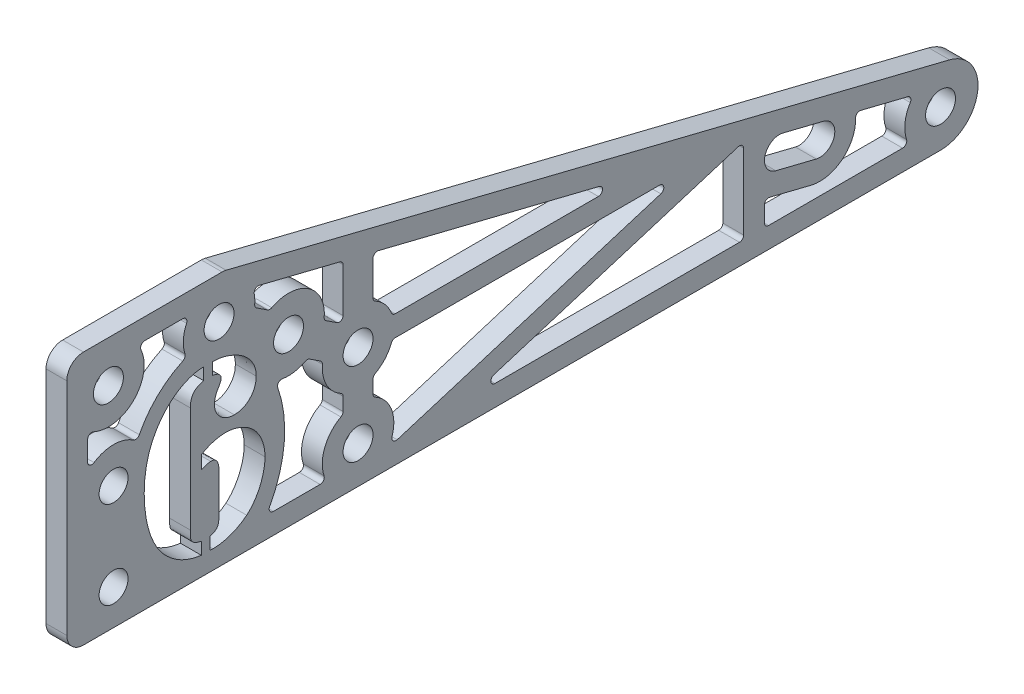
SolidWorks part; units mm, degrees
material "Acrylic (Medium-high impact)"
ref_plane "Front Plane" through (0, 0, 0) normal (0, 0, 1) x (1, 0, 0)
ref_plane "Top Plane" through (0, 0, 0) normal (0, 1, 0) x (1, 0, 0)
ref_plane "Right Plane" through (0, 0, 0) normal (1, 0, 0) x (0, 0, -1)
sketch "Sketch1" plane through (0, 0, 0) normal (1, 0, 0) x (0, 0, -1)
  line L0 (0, 6.35) -> (0, -6.35) construction
  line L1 (0, -6.35) -> (88.9, -6.35) construction
  line L2 (88.9, -6.35) -> (0, 6.35) construction
  line L3 (0, 6.35) -> (88.9, 6.35) construction
  line L4 (88.9, 6.35) -> (88.9, -6.35) construction
  line L5 (-20.1358, 26.5952) -> (90.2764, -0.8032)
  line L6 (0, -12.065) -> (88.9, -12.065)
  line L7 (-20.7475, 26.67) -> (-41.91, 26.67)
  line L8 (-44.45, 24.13) -> (-44.45, -9.525)
  line L9 (-41.91, -12.065) -> (0, -12.065)
  line L11 (0, 6.35) -> (-10.6066, 13.335) construction
  line L12 (-10.6066, 13.335) -> (-21.2132, 20.32) construction
  line L13 (-21.2132, 20.32) -> (-38.1, 20.32) construction
  circle A0 centre (0, 6.35) radius 2.286
  circle A1 centre (0, -6.35) radius 2.286
  circle A2 centre (88.9, -6.35) radius 2.286
  circle A3 centre (0, -6.35) radius 5.715 construction
  circle A4 centre (0, 6.35) radius 5.715 construction
  circle A5 centre (88.9, -6.35) radius 5.715 construction
  circle A6 centre (88.9, 6.35) radius 2.286 construction
  circle A7 centre (88.9, 6.35) radius 5.715 construction
  arc A8 (88.9, -12.065) -> (90.2764, -0.8032) centre (88.9, -6.35) ccw
  arc A9 (-20.7475, 26.67) -> (-20.1358, 26.5952) centre (-20.7475, 24.13) cw
  arc A10 (-44.45, -9.525) -> (-41.91, -12.065) centre (-41.91, -9.525) ccw
  arc A12 (-41.91, 26.67) -> (-44.45, 24.13) centre (-41.91, 24.13) ccw
  circle A13 centre (-21.2132, 20.32) radius 2.286
  circle A14 centre (-10.6066, 13.335) radius 2.286
  circle A15 centre (-38.1, 20.32) radius 2.286
  dimension "D1" = 4.572
  dimension "D4" = 11.43
  dimension "D5" = 2.54
  dimension "D7" = 6.35
  dimension "D9" = 32.385
  dimension "D11" = 6.35
  dimension "D2" = 12.7
  dimension "D3" = 88.9
  dimension "D6" = 44.45
  dimension "D8" = 6.35
  dimension "D10" = 12.7
extrude "Boss-Extrude1" add sketch "Sketch1" along normal blind 3.175
sketch "Sketch2" plane through (3.175, 0, 0) normal (1, 0, 0) x (0, 0, -1)
  line L0 (-35.1004, 12.065) -> (-44.45, 12.065) construction
  line L1 (-44.45, 24.13) -> (-44.45, -9.525) construction
  line L2 (-37.3103, 6.6801) -> (-37.3103, -6.6801) construction
  line L3 (-37.3103, 8.89) -> (-37.3103, 12.065) construction
  line L5 (-37.3103, -8.89) -> (-37.3103, -12.065) construction
  line L6 (-41.91, -12.065) -> (88.9, -12.065) construction
  line L7 (-35.1004, 12.065) -> (-35.1004, -12.065) construction
  line L8 (-39.5202, 12.065) -> (-39.5202, -12.065) construction
  line L9 (64.3105, 0.0135) -> (70.4736, -1.5158) construction
  line L10 (64.8611, 2.2322) -> (71.0241, 0.7029)
  line L11 (63.7599, -2.2052) -> (69.923, -3.7345)
  line L12 (90.2764, -0.8032) -> (-20.1358, 26.5952) construction
  circle A0 centre (-37.3103, 6.6801) radius 2.2099
  circle A1 centre (-37.3103, -6.6801) radius 2.2099
  circle A2 centre (0, -6.35) radius 2.286 construction
  arc A3 (64.8611, 2.2322) -> (63.7599, -2.2052) centre (64.3105, 0.0135) ccw
  arc A4 (69.923, -3.7345) -> (71.0241, 0.7029) centre (70.4736, -1.5158) ccw
  circle A5 centre (0, 6.35) radius 2.286 construction
  circle A6 centre (88.9, -6.35) radius 2.286 construction
  point P11 (67.392, -0.7512)
  dimension "D3" = 4.4198
  dimension "D1" = 3.175
  dimension "D2" = 35.1004
  dimension "D4" = 24.13
  dimension "D5" = 3.175
  dimension "D6" = 6.35
  dimension "D7" = 19.05
extrude "Cut-Extrude1" cut sketch "Sketch2" against normal through all
sketch "Sketch3" plane through (3.175, 0, 0) normal (1, 0, 0) x (0, 0, -1)
  line L0 (-41.275, 23.495) -> (-20.8251, 23.495) construction
  line L2 (-20.8251, 23.495) -> (88.9, -3.733) construction
  line L3 (88.9, -3.733) -> (88.9, -8.89) construction
  line L4 (88.9, -8.89) -> (-41.275, -8.89) construction
  line L5 (-41.275, -8.89) -> (-41.275, 23.495) construction
  line L6 (-44.45, 24.13) -> (-44.45, -9.525) construction
  line L9 (90.2764, -0.8032) -> (-20.1358, 26.5952) construction
  line L10 (-41.91, -12.065) -> (88.9, -12.065) construction
  line L11 (-20.7475, 26.67) -> (-41.91, 26.67) construction
  circle A0 centre (-37.3103, 6.6801) radius 5.461 construction
  circle A1 centre (-37.3103, -6.6801) radius 5.461 construction
  circle A2 centre (-10.6066, 13.335) radius 5.461 construction
  circle A3 centre (0, 6.35) radius 5.461 construction
  circle A4 centre (0, -6.35) radius 5.461 construction
  circle A5 centre (88.9, -6.35) radius 5.461 construction
  circle A6 centre (0, -6.35) radius 2.286 construction
  circle A7 centre (-21.2132, 20.32) radius 5.461 construction
  circle A8 centre (-21.2132, 20.32) radius 2.286 construction
  text T0 "6" font "Stencil" height 24.13
  point P8 (-31.3288, 26.67)
  point P14 (88.9, -6.35)
  dimension "D7" = 3.175
  dimension "D1" = 3.175
  dimension "D2" = 3.175
  dimension "D4" = 3.175
  dimension "D5" = 3.175
extrude "Cut-Extrude2" cut sketch "Sketch3" against normal through all
sketch "Sketch4" plane through (3.175, 0, 0) normal (1, 0, 0) x (0, 0, -1)
  line L0 (-41.275, 23.495) -> (-20.8251, 23.495) construction
  line L1 (-7.3953, 8.483) -> (-5.7259, 7.3836)
  line L2 (2.286, -0.9994) -> (2.286, 0.9994)
  line L3 (2.286, 11.7006) -> (2.286, 16.9482)
  line L4 (-2.286, 11.6673) -> (-2.286, 18.3979)
  line L5 (88.9, -3.733) -> (88.9, -8.89) construction
  line L6 (-41.275, -8.89) -> (-41.275, 23.495) construction
  line L7 (-4.8807, 12.3014) -> (-3.1835, 11.1837)
  line L8 (-13.8179, 18.187) -> (-15.4872, 19.2864)
  line L9 (-15.07, 22.0669) -> (-2.7681, 19.0142)
  line L10 (88.9, -8.89) -> (-41.275, -8.89) construction
  line L11 (88.9, -3.733) -> (88.9, -8.89) construction
  line L12 (-41.275, 14.7784) -> (-41.275, 11.7864)
  line L13 (-32.5584, 23.495) -> (-26.7548, 23.495)
  line L14 (5.6764, 7.9375) -> (36.674, 7.9375)
  line L15 (-12.9295, -8.89) -> (-5.7907, -8.89)
  line L16 (-2.286, 0.9994) -> (-2.286, -0.9994)
  line L17 (62.9952, -5.2867) -> (69.1583, -6.8161) construction
  line L18 (62.0245, -5.8577) -> (62.0245, -8.255)
  line L19 (76.7196, -0.7104) -> (83.8915, -2.4901)
  line L20 (62.6595, -8.89) -> (83.1093, -8.89)
  line L21 (62.8124, -5.2414) -> (69.1583, -6.8161)
  line L22 (20.9031, -8.89) -> (58.2145, -8.89)
  line L23 (-20.8251, 23.495) -> (88.9, -3.733) construction
  line L24 (5.6764, 4.7625) -> (46.0273, 4.7625)
  line L25 (3.0739, 17.5645) -> (36.8269, 9.1888)
  line L33 (0, 6.35) -> (5.6764, 6.35) construction
  line L34 (5.6764, 6.35) -> (5.6764, 7.9375) construction
  line L35 (5.6764, 6.35) -> (5.6764, 4.7625) construction
  line L36 (58.8495, 3.2273) -> (58.8495, -8.255)
  line L40 (5.9775, -8.8619) -> (46.2141, 3.5206)
  line L41 (58.0277, 3.8342) -> (20.7163, -7.6481)
  circle A0 centre (-37.3103, 6.6801) radius 5.461 construction
  circle A1 centre (-21.2132, 20.32) radius 5.461 construction
  arc A2 (62.0245, -5.8577) -> (62.8124, -5.2414) centre (62.6595, -5.8577) cw
  circle A4 centre (-38.1, 20.32) radius 5.461 construction
  circle A5 centre (-10.6066, 13.335) radius 5.461 construction
  circle A6 centre (88.9, -6.35) radius 5.461 construction
  arc A7 (-11.5416, 7.9546) -> (-8.0426, 8.5133) centre (-10.6066, 13.335) ccw
  circle A8 centre (-10.6066, 13.335) radius 2.286 construction
  circle A10 centre (0, -6.35) radius 5.461 construction
  circle A11 centre (0, 6.35) radius 5.461 construction
  circle A12 centre (0, 6.35) radius 2.286 construction
  arc A13 (-5.4424, 6.8009) -> (-5.7259, 7.3836) centre (-6.0752, 6.8533) ccw
  arc A14 (-40.2932, 11.2545) -> (-34.3002, 11.2366) centre (-37.3103, 6.6801) cw
  arc A15 (-26.1776, 22.5954) -> (-26.4174, 18.6651) centre (-21.2132, 20.32) ccw
  arc A16 (-26.7528, 17.8978) -> (-33.3843, 11.4781) centre (-20.7119, 5.0226) ccw
  arc A17 (-26.7548, 23.495) -> (-26.1776, 22.5954) centre (-26.7548, 22.86) cw
  arc A18 (-26.7528, 17.8978) -> (-26.4174, 18.6651) centre (-27.0225, 18.4727) ccw
  arc A19 (-33.3843, 11.4781) -> (-34.3002, 11.2366) centre (-33.9501, 11.7664) cw
  arc A20 (-41.275, 11.7864) -> (-40.2932, 11.2545) centre (-40.64, 11.7864) ccw
  arc A21 (-40.3754, 15.3556) -> (-33.1356, 22.5954) centre (-38.1, 20.32) ccw
  arc A22 (-12.2493, 7.1182) -> (-13.4861, -7.9493) centre (-29.7211, 0.9679) cw
  arc A23 (-5.4424, 6.8009) -> (-2.6167, 1.5567) centre (0, 6.35) ccw
  arc A24 (-2.6167, -1.5567) -> (-5.1875, -8.0566) centre (0, -6.35) ccw
  arc A25 (-8.0426, 8.5133) -> (-7.3953, 8.483) centre (-7.7445, 7.9527) cw
  arc A26 (2.6167, 1.5567) -> (5.0851, 4.359) centre (0, 6.35) ccw
  arc A27 (-13.4861, -7.9493) -> (-12.9295, -8.89) centre (-12.9295, -8.255) ccw
  arc A28 (-5.7907, -8.89) -> (-5.1875, -8.0566) centre (-5.7907, -8.255) ccw
  arc A29 (-2.286, -0.9994) -> (-2.6167, -1.5567) centre (-2.921, -0.9994) cw
  arc A30 (-2.6167, 1.5567) -> (-2.286, 0.9994) centre (-2.921, 0.9994) cw
  arc A31 (60.0475, 3.4267) -> (62.9952, -5.2867) centre (64.3105, 0.0135) ccw construction
  arc A32 (69.1583, -6.8161) -> (75.8377, -0.4916) centre (70.4736, -1.5158) ccw construction
  arc A33 (69.923, -3.7345) -> (71.0241, 0.7029) centre (70.4736, -1.5158) ccw construction
  arc A34 (64.8611, 2.2322) -> (63.7599, -2.2052) centre (64.3105, 0.0135) ccw construction
  arc A35 (75.9319, -1.3464) -> (69.1583, -6.8161) centre (70.4736, -1.5158) cw
  arc A36 (83.7125, -8.0566) -> (84.2762, -3.4443) centre (88.9, -6.35) cw
  arc A37 (62.0245, -8.255) -> (62.6595, -8.89) centre (62.6595, -8.255) ccw
  arc A38 (75.9319, -1.3464) -> (76.7196, -0.7104) centre (76.5666, -1.3267) cw
  arc A39 (84.2762, -3.4443) -> (83.8915, -2.4901) centre (83.7386, -3.1064) ccw
  arc A40 (83.1093, -8.89) -> (83.7125, -8.0566) centre (83.1093, -8.255) ccw
  arc A43 (5.1875, -8.0566) -> (2.6167, -1.5567) centre (0, -6.35) ccw
  arc A45 (2.6167, 11.1433) -> (2.286, 11.7006) centre (2.921, 11.7006) cw
  arc A48 (20.9031, -8.89) -> (20.7163, -7.6481) centre (20.9031, -8.255) cw
  arc A49 (3.0739, 17.5645) -> (2.286, 16.9482) centre (2.921, 16.9482) ccw
  arc A50 (2.286, 0.9994) -> (2.6167, 1.5567) centre (2.921, 0.9994) cw
  arc A52 (2.6167, -1.5567) -> (2.286, -0.9994) centre (2.921, -0.9994) cw
  arc A53 (-15.7708, 19.8691) -> (-15.8469, 21.3328) centre (-21.2132, 20.32) ccw
  arc A55 (-5.1642, 12.8841) -> (-13.1705, 18.1567) centre (-10.6066, 13.335) ccw
  arc A56 (-11.5416, 7.9546) -> (-12.2493, 7.1182) centre (-11.6503, 7.329) ccw
  arc A59 (-40.3754, 15.3556) -> (-41.275, 14.7784) centre (-40.64, 14.7784) ccw
  arc A60 (-33.1356, 22.5954) -> (-32.5584, 23.495) centre (-32.5584, 22.86) cw
  circle A61 centre (-38.1, 20.32) radius 2.286 construction
  arc A62 (-4.8807, 12.3014) -> (-5.1642, 12.8841) centre (-4.5314, 12.8317) cw
  arc A63 (-2.286, 18.3979) -> (-2.7681, 19.0142) centre (-2.921, 18.3979) ccw
  arc A64 (-15.8469, 21.3328) -> (-15.07, 22.0669) centre (-15.2229, 21.4506) cw
  arc A65 (-13.1705, 18.1567) -> (-13.8179, 18.187) centre (-13.4687, 18.7173) cw
  arc A66 (-15.4872, 19.2864) -> (-15.7708, 19.8691) centre (-15.138, 19.8167) cw
  arc A67 (-3.1835, 11.1837) -> (-2.286, 11.6673) centre (-2.865, 11.6673) ccw
  arc A68 (5.0851, 8.341) -> (2.6167, 11.1433) centre (0, 6.35) ccw
  arc A69 (5.6764, 4.7625) -> (5.0851, 4.359) centre (5.6764, 4.1275) ccw
  arc A71 (36.674, 7.9375) -> (36.8269, 9.1888) centre (36.674, 8.5725) ccw
  arc A72 (5.6764, 7.9375) -> (5.0851, 8.341) centre (5.6764, 8.5725) cw
  arc A75 (58.8495, -8.255) -> (58.2145, -8.89) centre (58.2145, -8.255) cw
  arc A76 (5.1875, -8.0566) -> (5.9775, -8.8619) centre (5.7907, -8.255) ccw
  arc A77 (46.0273, 4.7625) -> (46.2141, 3.5206) centre (46.0273, 4.1275) cw
  arc A78 (58.8495, 3.2273) -> (58.0277, 3.8342) centre (58.2145, 3.2273) ccw
  point P36 (-25.6564, 23.495)
  point P39 (-26.2182, 18.1354)
  point P42 (-33.7126, 10.7885)
  point P45 (-41.275, 10.4356)
  point P66 (-4.8343, -8.89)
  point P69 (-2.286, -1.3905)
  point P72 (-2.286, 1.3905)
  point P92 (-5.3993, 7.1685)
  point P126 (60.0475, 3.4267)
  point P131 (2.286, 17.76)
  point P134 (2.286, 1.3905)
  point P139 (2.286, -1.3905)
  point P175 (-5.2073, 12.5165)
  point P178 (-2.286, 18.8946)
  point P181 (-16.1361, 22.3314)
  point P184 (-13.4913, 17.9719)
  point P187 (-15.8139, 19.5015)
  point P202 (5.2252, 7.9375)
  dimension "D1" = 3.175
  dimension "D2" = 0.635
  dimension "D4" = 3.175
  dimension "D6" = 3.175
  dimension "D3" = 3.175
extrude "Cut-Extrude3" cut sketch "Sketch4" against normal through all
